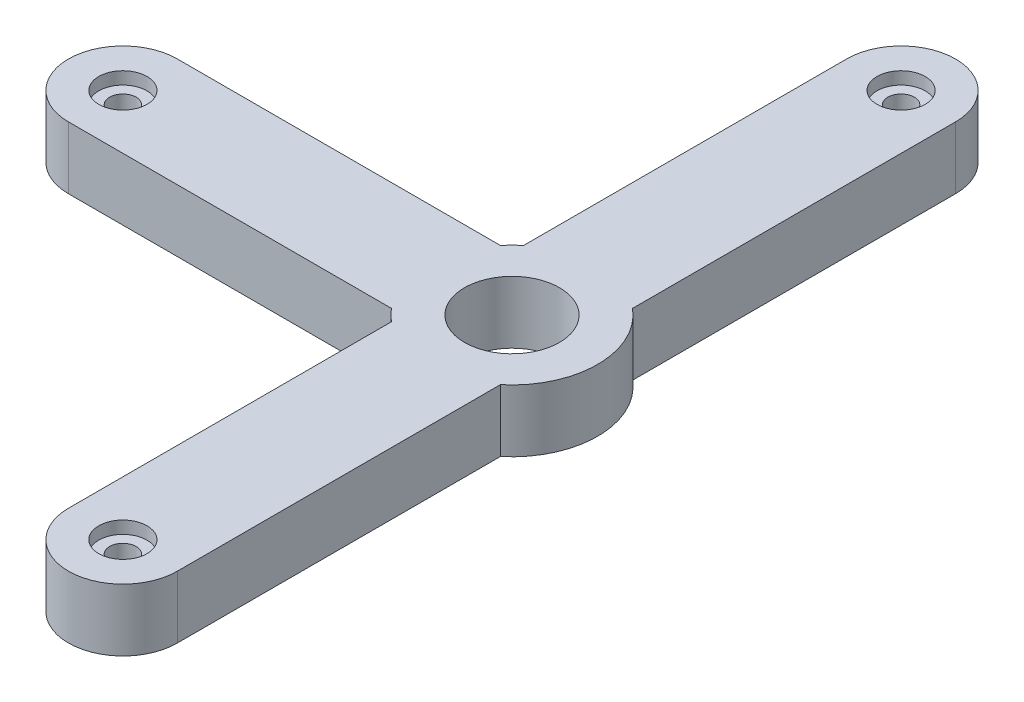
SolidWorks part; units mm, degrees
other "Rear Support Plate Print Blank"
ref_plane "Front Plane" through (0, 0, 0) normal (0, 0, 1) x (1, 0, 0)
ref_plane "Top Plane" through (0, 0, 0) normal (0, 1, 0) x (1, 0, 0)
ref_plane "Right Plane" through (0, 0, 0) normal (1, 0, 0) x (0, 0, -1)
sketch3d "Base Outline Sketch datum points"
  point P0 (0, -157, 0)
  point P1 (10, -157, 0)
  point P2 (0, -157, -10)
ref_plane "Base Outline Sketch plane" through (0, -157, 0) normal (0, 1, 0) x (1, 0, 0)
sketch "Base Outline Sketch" plane through (0, -157, 0) normal (0, 1, 0) x (1, 0, 0)
  line L0 (-106.2917, -7) -> (-64.7769, -7)
  line L1 (-63.2917, -8.4853) -> (-63.2917, -50)
  line L2 (-49.2917, -50) -> (-49.2917, -8.4853)
  line L3 (-49.2917, 8.4853) -> (-49.2917, 50)
  line L4 (-63.2917, 50) -> (-63.2917, 8.4853)
  line L5 (-64.7769, 7) -> (-106.2917, 7)
  arc A0 (-106.2917, 7) -> (-106.2917, -7) centre (-106.2917, 0) ccw
  arc A1 (-64.7769, -7) -> (-63.2917, -8.4853) centre (-56.2917, 0) ccw
  arc A2 (-63.2917, -50) -> (-49.2917, -50) centre (-56.2917, -50) ccw
  arc A3 (-49.2917, -8.4853) -> (-49.2917, 8.4853) centre (-56.2917, 0) ccw
  arc A4 (-49.2917, 50) -> (-63.2917, 50) centre (-56.2917, 50) ccw
  arc A5 (-63.2917, 8.4853) -> (-64.7769, 7) centre (-56.2917, 0) ccw
  circle A6 centre (-106.2917, 0) radius 1.7
  circle A7 centre (-56.2917, 50) radius 1.7
  circle A8 centre (-56.2917, 0) radius 6.1
  circle A9 centre (-56.2917, -50) radius 1.7
  circle A10 centre (-65.2917, 0) radius 1.6
  circle A11 centre (-56.2917, -9) radius 1.6
  circle A12 centre (-56.2917, 9) radius 1.6
extrude "Base Outline" add sketch "Base Outline Sketch" along normal blind 4 separate body
sketch3d "Interface Profile 2 Sketch datum points"
  point P0 (0, -153, 0)
  point P1 (10, -153, 0)
  point P2 (0, -153, -10)
ref_plane "Interface Profile 2 Sketch plane" through (0, -153, 0) normal (0, 1, 0) x (1, 0, 0)
sketch "Interface Profile 2 Sketch" plane through (0, -153, 0) normal (0, 1, 0) x (1, 0, 0)
  line L0 (-106.2917, -7) -> (-64.7769, -7)
  line L1 (-63.2917, -8.4853) -> (-63.2917, -50)
  line L2 (-49.2917, -50) -> (-49.2917, -8.4853)
  line L3 (-49.2917, 8.4853) -> (-49.2917, 50)
  line L4 (-63.2917, 50) -> (-63.2917, 8.4853)
  line L5 (-64.7769, 7) -> (-106.2917, 7)
  arc A0 (-106.2917, 7) -> (-106.2917, -7) centre (-106.2917, 0) ccw
  arc A1 (-64.7769, -7) -> (-63.2917, -8.4853) centre (-56.2917, 0) ccw
  arc A2 (-63.2917, -50) -> (-49.2917, -50) centre (-56.2917, -50) ccw
  arc A3 (-49.2917, -8.4853) -> (-49.2917, 8.4853) centre (-56.2917, 0) ccw
  arc A4 (-49.2917, 50) -> (-63.2917, 50) centre (-56.2917, 50) ccw
  arc A5 (-63.2917, 8.4853) -> (-64.7769, 7) centre (-56.2917, 0) ccw
  circle A6 centre (-106.2917, 0) radius 1.7
  circle A7 centre (-56.2917, 50) radius 1.7
  circle A8 centre (-56.2917, 0) radius 6.1
  circle A9 centre (-56.2917, -50) radius 1.7
  circle A10 centre (-65.2917, 0) radius 1.1
  circle A11 centre (-56.2917, -9) radius 1.1
  circle A12 centre (-56.2917, 9) radius 1.1
extrude "Interface Profile 2" add sketch "Interface Profile 2 Sketch" along normal blind 2.4
sketch3d "Interface Profile 3 Sketch datum points"
  point P0 (0, -150.6, 0)
  point P1 (10, -150.6, 0)
  point P2 (0, -150.6, -10)
ref_plane "Interface Profile 3 Sketch plane" through (0, -150.6, 0) normal (0, 1, 0) x (1, 0, 0)
sketch "Interface Profile 3 Sketch" plane through (0, -150.6, 0) normal (0, 1, 0) x (1, 0, 0)
  line L0 (-106.2917, -7) -> (-64.7769, -7)
  line L1 (-63.2917, -8.4853) -> (-63.2917, -50)
  line L2 (-49.2917, -50) -> (-49.2917, -8.4853)
  line L3 (-49.2917, 8.4853) -> (-49.2917, 50)
  line L4 (-63.2917, 50) -> (-63.2917, 8.4853)
  line L5 (-64.7769, 7) -> (-106.2917, 7)
  arc A0 (-106.2917, 7) -> (-106.2917, -7) centre (-106.2917, 0) ccw
  arc A1 (-64.7769, -7) -> (-63.2917, -8.4853) centre (-56.2917, 0) ccw
  arc A2 (-63.2917, -50) -> (-49.2917, -50) centre (-56.2917, -50) ccw
  arc A3 (-49.2917, -8.4853) -> (-49.2917, 8.4853) centre (-56.2917, 0) ccw
  arc A4 (-49.2917, 50) -> (-63.2917, 50) centre (-56.2917, 50) ccw
  arc A5 (-63.2917, 8.4853) -> (-64.7769, 7) centre (-56.2917, 0) ccw
  circle A6 centre (-56.2917, 0) radius 6.1
  circle A7 centre (-106.2917, 0) radius 3.1
  circle A8 centre (-56.2917, 50) radius 3.1
  circle A9 centre (-56.2917, -50) radius 3.1
  circle A10 centre (-65.2917, 0) radius 1.1
  circle A11 centre (-56.2917, -9) radius 1.1
  circle A12 centre (-56.2917, 9) radius 1.1
extrude "Interface Profile 3" add sketch "Interface Profile 3 Sketch" along normal blind 0.6
sketch3d "Interface Profile 4 Sketch datum points"
  point P0 (0, -150, 0)
  point P1 (10, -150, 0)
  point P2 (0, -150, -10)
ref_plane "Interface Profile 4 Sketch plane" through (0, -150, 0) normal (0, 1, 0) x (1, 0, 0)
sketch "Interface Profile 4 Sketch" plane through (0, -150, 0) normal (0, 1, 0) x (1, 0, 0)
  line L0 (-106.2917, -7) -> (-64.7769, -7)
  line L1 (-63.2917, -8.4853) -> (-63.2917, -50)
  line L2 (-49.2917, -50) -> (-49.2917, -8.4853)
  line L3 (-49.2917, 8.4853) -> (-49.2917, 50)
  line L4 (-63.2917, 50) -> (-63.2917, 8.4853)
  line L5 (-64.7769, 7) -> (-106.2917, 7)
  arc A0 (-106.2917, 7) -> (-106.2917, -7) centre (-106.2917, 0) ccw
  arc A1 (-64.7769, -7) -> (-63.2917, -8.4853) centre (-56.2917, 0) ccw
  arc A2 (-63.2917, -50) -> (-49.2917, -50) centre (-56.2917, -50) ccw
  arc A3 (-49.2917, -8.4853) -> (-49.2917, 8.4853) centre (-56.2917, 0) ccw
  arc A4 (-49.2917, 50) -> (-63.2917, 50) centre (-56.2917, 50) ccw
  arc A5 (-63.2917, 8.4853) -> (-64.7769, 7) centre (-56.2917, 0) ccw
  circle A6 centre (-56.2917, 0) radius 6.1
  circle A7 centre (-106.2917, 0) radius 3.1
  circle A8 centre (-56.2917, 50) radius 3.1
  circle A9 centre (-56.2917, -50) radius 3.1
extrude "Interface Profile 4" add sketch "Interface Profile 4 Sketch" along normal blind 1
